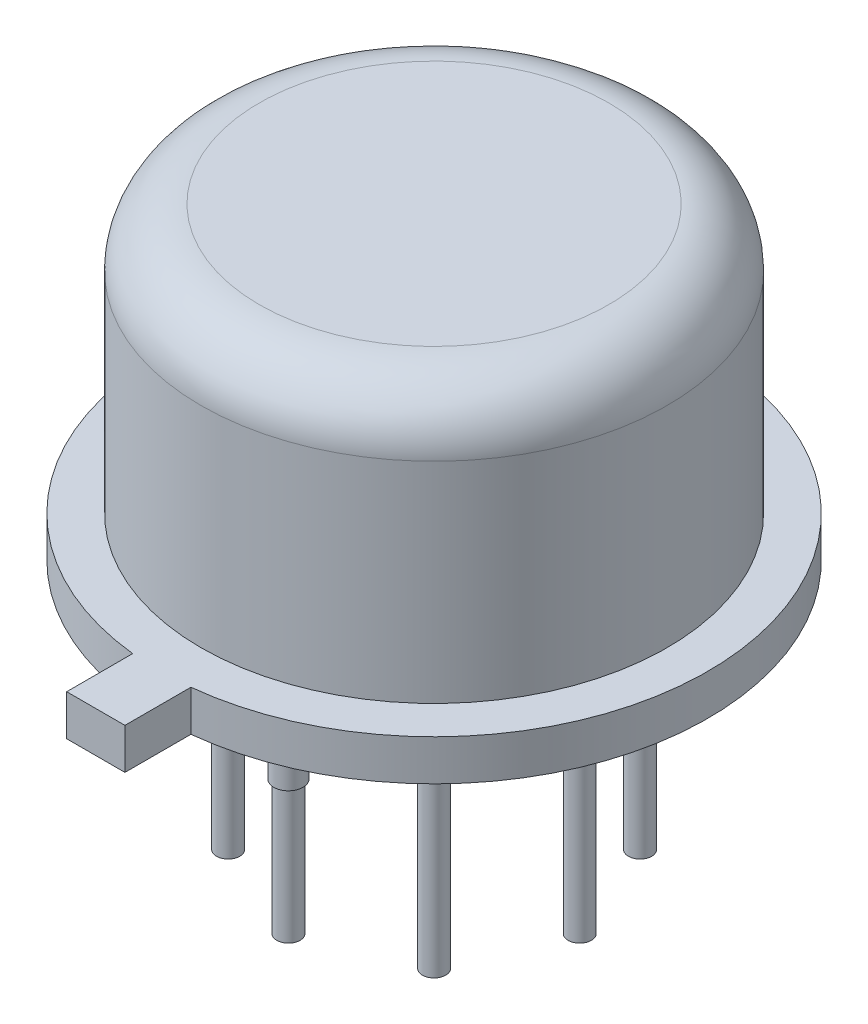
SolidWorks part; units mm, degrees
ref_plane "Спереди" through (0, 0, 0) normal (0, 0, 1) x (1, 0, 0)
ref_plane "Сверху" through (0, 0, 0) normal (0, 1, 0) x (1, 0, 0)
ref_plane "Справа" through (0, 0, 0) normal (1, 0, 0) x (0, 0, -1)
sketch "Эскиз1" plane through (0, 0, 0) normal (0, 1, 0) x (1, 0, 0)
  line L1 (0, -5.8061) -> (0.5, -5.8061)
  line L2 (0.5, -5.8061) -> (0.5, -4.6733)
  line L3 (0, -5.8061) -> (-0.5, -5.8061)
  line L4 (-0.5, -5.8061) -> (-0.5, -4.6733)
  arc A0 (0.5, -4.6733) -> (-0.5, -4.6733) centre (0, 0) ccw
extrude "Бобышка-Вытянуть1" add sketch "Эскиз1" along normal blind 0.7
sketch "Эскиз2" plane through (0, 0.7, 0) normal (0, 1, 0) x (1, 0, 0)
  circle A0 centre (0, 0) radius 4
extrude "Бобышка-Вытянуть2" add sketch "Эскиз2" along normal blind 4.6
fillet "Скругление1" radius 1 1 edges at (0, 5.3, 4)
sketch "Эскиз4" plane through (0, 0, 0) normal (0, -1, 0) x (1, 0, 0)
  circle A2 centre (2.5, 0) radius 0.2
  circle A3 centre (1.7678, -1.7678) radius 0.2
  circle A4 centre (0, -2.5) radius 0.2
  circle A5 centre (-1.7678, -1.7678) radius 0.2
  circle A6 centre (-2.5, 0) radius 0.2
  circle A7 centre (-1.7678, 1.7678) radius 0.2
  circle A8 centre (0, 2.5) radius 0.2
  circle A9 centre (1.7678, 1.7678) radius 0.2
extrude "Бобышка-Вытянуть3" add sketch "Эскиз4" along normal blind 4.3
sketch "Эскиз5" plane through (0, 0, 0) normal (0, -1, 0) x (1, 0, 0)
  circle A0 centre (0, 2.5) radius 0.25
extrude "Бобышка-Вытянуть4" add sketch "Эскиз5" along normal blind 2
